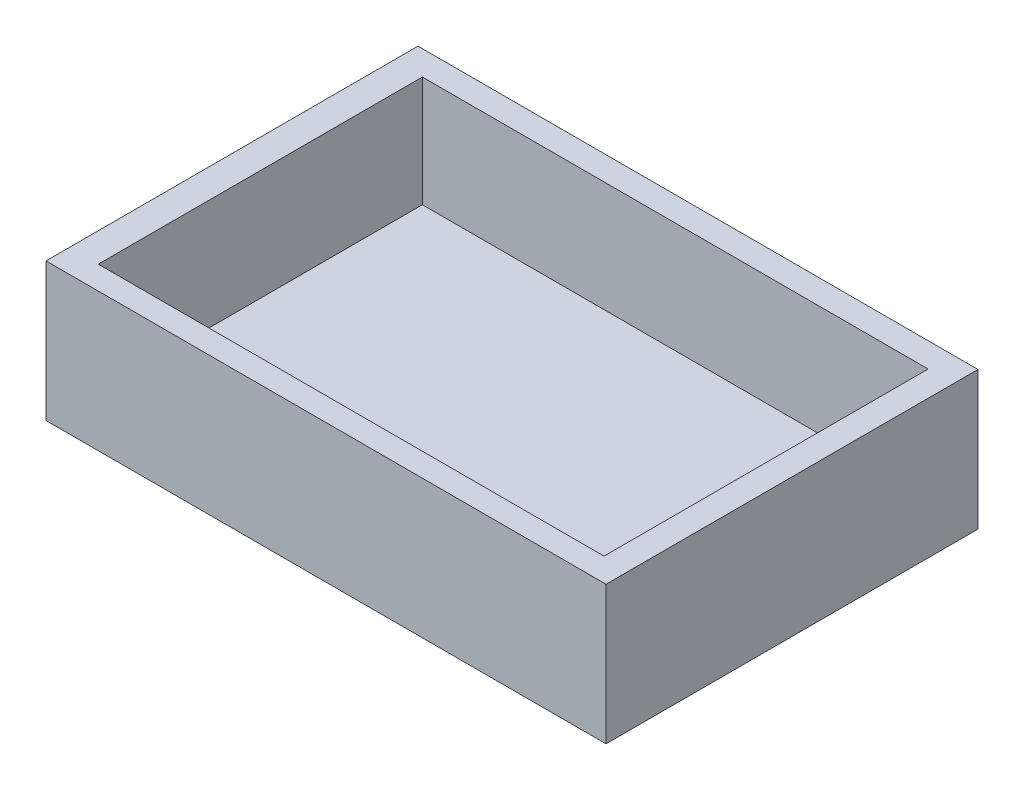
SolidWorks part; units mm, degrees
ref_plane "Front Plane" through (0, 0, 0) normal (0, 0, 1) x (1, 0, 0)
ref_plane "Top Plane" through (0, 0, 0) normal (0, 1, 0) x (1, 0, 0)
ref_plane "Right Plane" through (0, 0, 0) normal (1, 0, 0) x (0, 0, -1)
sketch "Sketch1" plane through (0, 0, 0) normal (0, 1, 0) x (1, 0, 0)
  line L1 (-102.5087, 57.2113) -> (100.0267, 57.2113)
  line L2 (-102.5087, 57.2113) -> (-102.5087, -77.3159)
  line L3 (-102.5087, -77.3159) -> (100.0267, -77.3159)
  line L4 (100.0267, 57.2113) -> (100.0267, -77.3159)
extrude "Boss-Extrude1" add sketch "Sketch1" along normal blind 50
sketch "Sketch2" plane through (0, 50, 0) normal (0, 1, 0) x (1, 0, 0)
  line L1 (-92.0357, 48.3313) -> (90.8632, 48.3313)
  line L2 (-92.0357, 48.3313) -> (-92.0357, -68.8724)
  line L3 (-92.0357, -68.8724) -> (90.8632, -68.8724)
  line L4 (90.8632, 48.3313) -> (90.8632, -68.8724)
extrude "Cut-Extrude1" cut sketch "Sketch2" against normal blind 40
